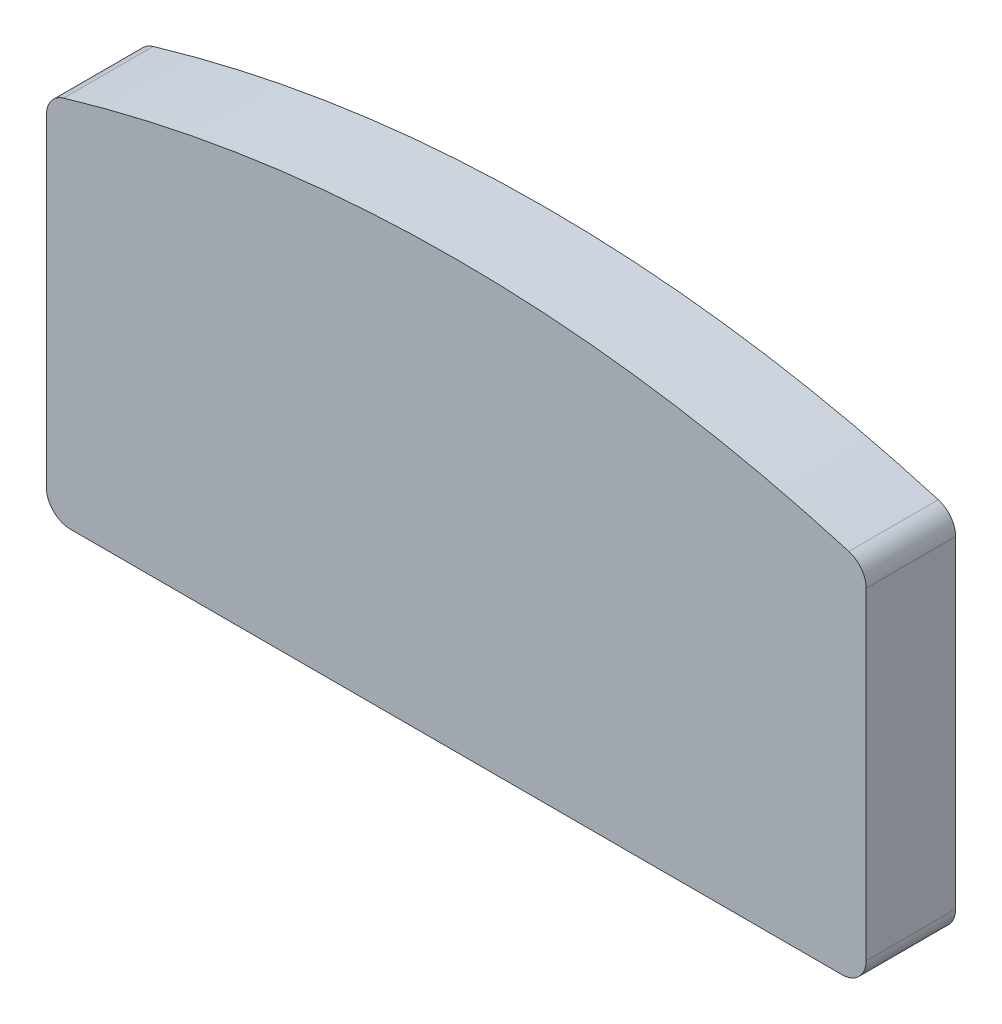
SolidWorks part; units mm, degrees
ref_plane "Front Plane" through (0, 0, 0) normal (0, 0, 1) x (1, 0, 0)
ref_plane "Top Plane" through (0, 0, 0) normal (0, 1, 0) x (1, 0, 0)
ref_plane "Right Plane" through (0, 0, 0) normal (1, 0, 0) x (0, 0, -1)
sketch "Sketch1" plane through (0, 0, 0) normal (0, 0, 1) x (1, 0, 0)
  line L0 (26.8, -44.15) -> (33.8, -44.15)
  line L1 (-33.8, -1.95) -> (-11.0544, -1.95)
  line L2 (-34.8, -2.95) -> (-34.8, -43.15)
  line L3 (-33.8, -44.15) -> (-26.8, -44.15)
  line L4 (34.8, -2.95) -> (34.8, -43.15)
  line L5 (0, -41.75) -> (34.8, -41.75) construction
  line L6 (11.0544, -1.95) -> (33.8, -1.95)
  circle A0 centre (0, 0) radius 1.95
  arc A1 (7.3532, 1.1973) -> (-7.3532, 1.1973) centre (0, 0) ccw
  arc A2 (-26.8, -44.15) -> (26.8, -44.15) centre (0, -192.5833) cw
  arc A3 (-34.8, -43.15) -> (-33.8, -44.15) centre (-33.8, -43.15) ccw
  arc A4 (-33.8, -1.95) -> (-34.8, -2.95) centre (-33.8, -2.95) ccw
  arc A5 (33.8, -1.95) -> (34.8, -2.95) centre (33.8, -2.95) cw
  arc A6 (33.8, -44.15) -> (34.8, -43.15) centre (33.8, -43.15) ccw
  arc A7 (-7.3532, 1.1973) -> (-11.0544, -1.95) centre (-11.0544, 1.8) cw
  arc A8 (7.3532, 1.1973) -> (11.0544, -1.95) centre (11.0544, 1.8) ccw
  point P12 (-34.8, -44.15)
  point P23 (34.8, -44.15)
  point P28 (7.1903, -1.95)
  dimension "D3" = 3.9
  dimension "D6" = 34.8
  dimension "D8" = 1
  dimension "D9" = 3.75
  dimension "D10" = 5.5
  dimension "D1" = 69.6
  dimension "D2" = 42.2
  dimension "D4" = 8
  dimension "D5" = 8
  dimension "D7" = 2.4
extrude "Extrude1" add sketch "Sketch1" along normal blind 3.8
sketch "Sketch2" plane through (0, 0, 0) normal (0, 0, -1) x (-1, 0, 0)
  line L0 (0, -5.1) -> (33.9, -5.1) construction
  line L1 (33.8, -44.15) -> (26.8, -44.15) construction
  line L2 (-33.9, -11.7179) -> (-33.9, -38.4)
  line L3 (-31.9, -40.4) -> (31.9, -40.4)
  line L4 (33.9, -11.7179) -> (33.9, -38.4)
  line L5 (-33.8, -1.95) -> (-11.0544, -1.95) construction
  arc A0 (-32.4672, -9.8) -> (32.4672, -9.8) centre (0, -119.5901) cw
  arc A2 (-33.9, -38.4) -> (-31.9, -40.4) centre (-31.9, -38.4) ccw
  arc A3 (31.9, -40.4) -> (33.9, -38.4) centre (31.9, -38.4) ccw
  arc A4 (32.4672, -9.8) -> (33.9, -11.7179) centre (31.9, -11.7179) cw
  arc A5 (-32.4672, -9.8) -> (-33.9, -11.7179) centre (-31.9, -11.7179) ccw
  arc A6 (26.8, -44.15) -> (-26.8, -44.15) centre (0, -192.5833) ccw construction
  point P22 (0, -41.75)
  dimension "D3" = 2
  dimension "D6" = 114.4901
  dimension "D1" = 3.75
  dimension "D2" = 67.8
  dimension "D4" = 35.3
  dimension "D5" = 30.6
  dimension "D7" = 7.85
  dimension "D8" = 1.35
extrude "Extrude2" add sketch "Sketch2" along normal blind 7.4
sketch "Sketch4" plane through (0, 0, 3.8) normal (0, 0, 1) x (1, 0, 0)
  line L0 (-23, -13.95) -> (23, -13.95) construction
  line L1 (0, -28.95) -> (0, -23.95) construction
  line L2 (-9.5, -18.95) -> (9.5, -18.95) construction
  line L3 (0, -23.95) -> (0, -18.95) construction
  line L4 (-13, -23.95) -> (13, -23.95) construction
  line L5 (0, -18.95) -> (0, -13.95) construction
  line L6 (-4.5, -28.95) -> (4.5, -28.95) construction
  line L7 (-11.0544, -1.95) -> (-33.8, -1.95) construction
  text T0 "Willwood Polymatrix"
  text T1 "1SH8596\r\n"
  text T2 "J306 6211H"
  text T3 "NRS\r\n"
  dimension "D1" = 12
  dimension "D2" = 5
  dimension "D3" = 5
  dimension "D4" = 5
  dimension "D5" = 46
  dimension "D6" = 19
  dimension "D7" = 26
  dimension "D8" = 9
sketch "Sketch5" plane through (0, 0, 3.8) normal (0, 0, 1) x (1, 0, 0)
  line L1 (-46.6996, 13.2869) -> (46.6996, 13.2869)
  line L2 (-46.6996, 13.2869) -> (-46.6996, -58.9831)
  line L3 (-46.6996, -58.9831) -> (46.6996, -58.9831)
  line L4 (46.6996, 13.2869) -> (46.6996, -58.9831)
  line L5 (-46.6996, 13.2869) -> (46.6996, -58.9831) construction
  line L6 (-46.6996, -58.9831) -> (46.6996, 13.2869) construction
  point P0 (0, -22.8481)
extrude "Cut-Extrude1" cut sketch "Sketch4" against normal blind 0.5
extrude "Cut-Extrude2" cut sketch "Sketch5" against normal blind 3.8
